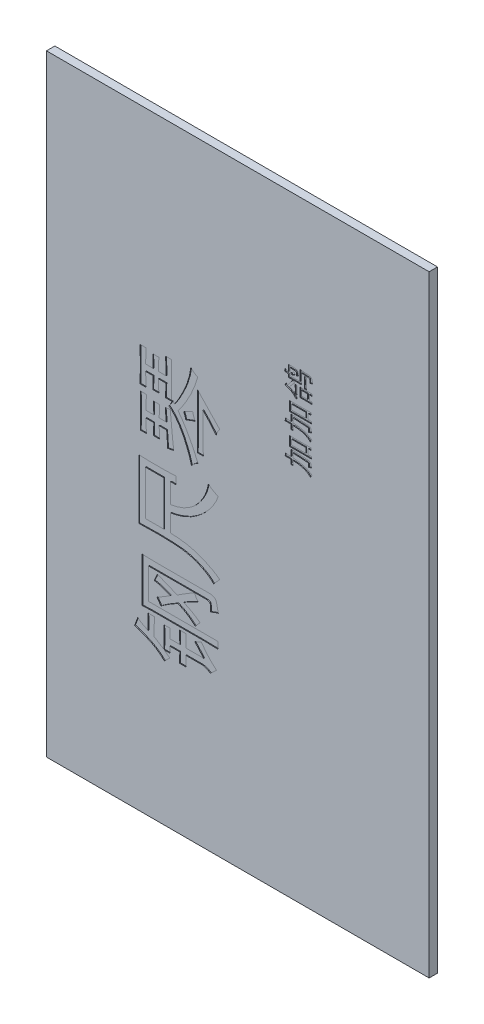
SolidWorks part; units mm, degrees
ref_plane "前视基准面" through (0, 0, 0) normal (0, 0, 1) x (1, 0, 0)
ref_plane "上视基准面" through (0, 0, 0) normal (0, 1, 0) x (1, 0, 0)
ref_plane "右视基准面" through (0, 0, 0) normal (1, 0, 0) x (0, 0, -1)
other "Configuration Table"
sketch "草图1" plane through (0, 0, 0) normal (0, 0, 1) x (1, 0, 0)
  line L4 (-66.1299, -22.38) -> (25.29, -22.38)
  line L5 (25.29, -22.38) -> (25.29, 123.75)
  line L6 (25.29, 123.75) -> (-66.1299, 123.75)
  line L7 (-66.1299, 123.75) -> (-66.1299, -22.38)
  line L8 (-66.1299, -22.38) -> (25.29, -22.38)
  line L9 (25.29, -22.38) -> (25.29, 123.75)
  line L10 (25.29, 123.75) -> (-66.1299, 123.75)
  line L11 (-66.1299, 123.75) -> (-66.1299, -22.38)
  dimension "D1" = 0
extrude "凸台-拉伸1" add sketch "草图1" along normal blind 2
sketch "草图4" plane through (0, 0, 2) normal (0, 0, 1) x (1, 0, 0)
  line L0 (-27.1234, 76.2375) -> (-27.1234, -7.318) construction
  line L1 (-3.3391, 66.7419) -> (-3.3391, 102.5918) construction
  text T0 "钢尺琴" font "黑体" height in points 48
  text T1 "加加鸽" font "黑体" height in points 16
  point P4 (0, 66.7419)
  point P5 (0, 102.5918)
extrude "切除-拉伸1" cut sketch "草图4" against normal blind 0.2
